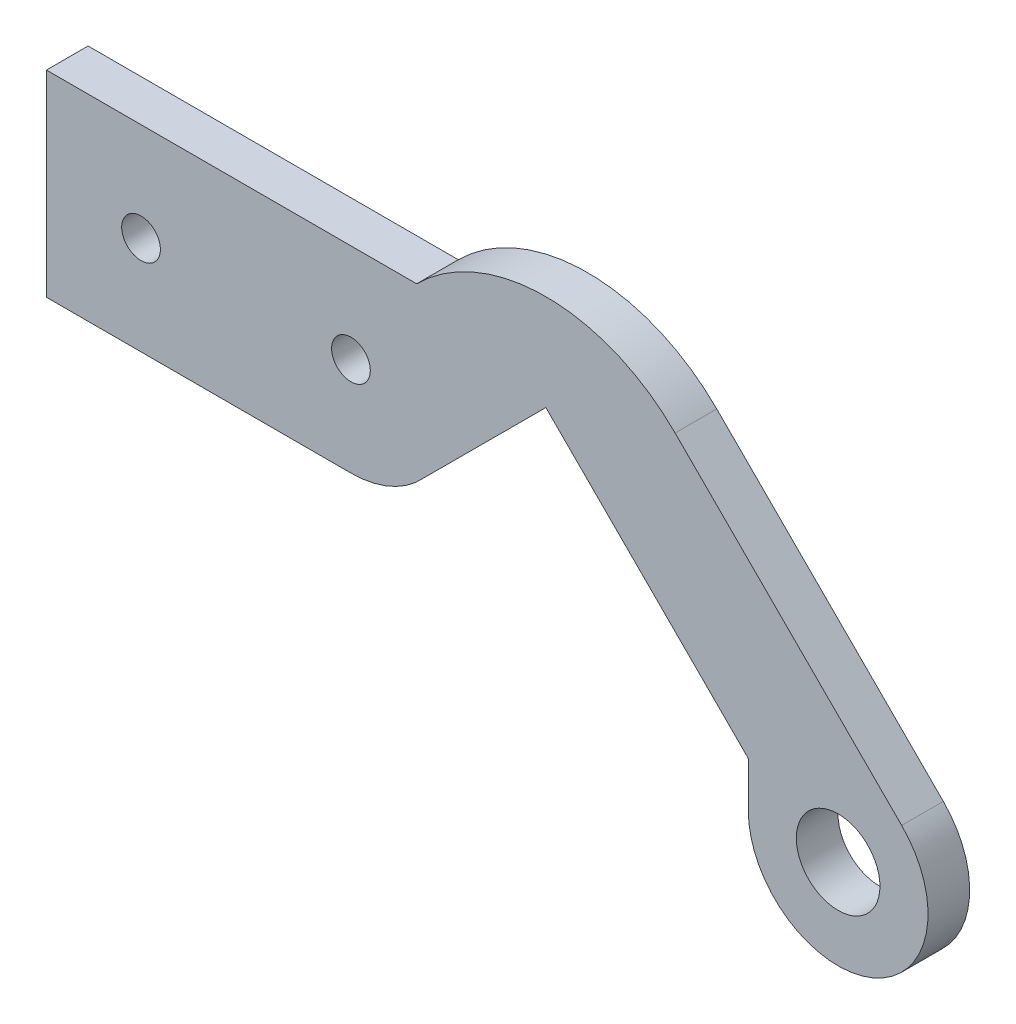
SolidWorks part; units mm, degrees
ref_plane "Front Plane" through (0, 0, 0) normal (0, 0, 1) x (1, 0, 0)
ref_plane "Top Plane" through (0, 0, 0) normal (0, 1, 0) x (1, 0, 0)
ref_plane "Right Plane" through (0, 0, 0) normal (1, 0, 0) x (0, 0, -1)
sketch "Sketch1" plane through (0, 0, 0) normal (0, 0, 1) x (1, 0, 0)
  line L0 (-37.5, 0) -> (37.5, 0)
  line L1 (-37.5, 0) -> (37.5, 0) construction
  line L2 (-37.5, 7.5) -> (37.5, 7.5)
  line L3 (-37.5, -7.5) -> (37.5, -7.5)
  arc A0 (-37.5, 7.5) -> (-37.5, -7.5) centre (-37.5, 0) ccw
  arc A1 (37.5, -7.5) -> (37.5, 7.5) centre (37.5, 0) ccw
  circle A2 centre (-37.5, 0) radius 3.175
  circle A3 centre (37.5, 0) radius 4.8
  point P0 (0, 0)
  point P4 (0, 0)
  dimension "D1" = 6.35
  dimension "D2" = 9.6
  dimension "D3" = 7.5
  dimension "D4" = 75
extrude "Boss-Extrude1" add sketch "Sketch1" along normal blind 3.175
sketch "Sketch2" plane through (0, 0, 3.175) normal (0, 0, 1) x (1, 0, 0)
  line L1 (-25, -1.3705) -> (-10, -1.3705)
  line L2 (-25, -1.3705) -> (-25, 1.8045)
  line L3 (-25, 1.8045) -> (-10, 1.8045)
  line L4 (-10, -1.3705) -> (-10, 1.8045)
  line L5 (-25, -1.3705) -> (-10, 1.8045) construction
  line L6 (-25, 1.8045) -> (-10, -1.3705) construction
  line L7 (10, -0.734) -> (25, -0.734)
  line L8 (10, -0.734) -> (10, 2.441)
  line L9 (10, 2.441) -> (25, 2.441)
  line L10 (25, -0.734) -> (25, 2.441)
  line L11 (10, -0.734) -> (25, 2.441) construction
  line L12 (10, 2.441) -> (25, -0.734) construction
  point P0 (-17.5, 0.217)
  point P5 (17.5, 0.8535)
  dimension "D1" = 3.175
  dimension "D2" = 3.175
  dimension "D3" = 15
  dimension "D4" = 15
  dimension "D5" = 20
  dimension "D6" = 10
extrude "Cut-Extrude1" cut sketch "Sketch2" against normal through all contours L2 L1 L4 L3 | L8 L7 L10 L9
sketch "Sketch3" plane through (0, 0, 3.175) normal (0, 0, 1) x (1, 0, 0)
  line L0 (-37.5, 0) -> (-20.71, 0)
  line L2 (-20.71, 0) -> (-56.5053, 0)
  line L3 (-20.71, 0) -> (-20.71, 17.1285)
  line L4 (-20.71, 17.1285) -> (-56.5053, 17.1285)
  line L5 (-56.5053, 0) -> (-56.5053, 17.1285)
  line L6 (-20.71, 0) -> (-56.5053, 0)
  line L7 (-20.71, 0) -> (-20.71, -10.2398)
  line L8 (-20.71, -10.2398) -> (-56.5053, -10.2398)
  line L9 (-56.5053, 0) -> (-56.5053, -10.2398)
  circle M3 centre (-37.5, 0) radius 3.175
  line M4 (-37.5, -7.5) -> (37.5, -7.5)
  line M6 (37.5, 7.5) -> (-37.5, 7.5)
  arc M7 (-37.5, 7.5) -> (-37.5, -7.5) centre (-37.5, 0) ccw
  line M12 (-25, -1.3705) -> (-25, 1.8045)
  line M13 (-25, 1.8045) -> (-10, 1.8045)
  line M15 (-10, -1.3705) -> (-25, -1.3705)
  dimension "D1" = 16.79
extrude "Cut-Extrude2" cut sketch "Sketch3" against normal blind 10 contours L5 L2 L3 L4 M7 M6 | L2 L9 L8 L7 M4 M7 | L3 L2 L0 M13 M6 M7 M3 M12 | L7 L0 L2 M15 M12 M3 M7 M4
sketch "Sketch4" plane through (0, 0, 3.175) normal (0, 0, 1) x (1, 0, 0)
  line L0 (-20.71, 1.8045) -> (-20.71, 7.5) construction
  line L1 (-20.71, 2.6568) -> (-9.1283, 2.6568)
  line L2 (-20.71, 2.6568) -> (-20.71, -2.9164)
  line L3 (-20.71, -2.9164) -> (-9.1283, -2.9164)
  line L4 (-9.1283, 2.6568) -> (-9.1283, -2.9164)
extrude "Boss-Extrude2" add sketch "Sketch4" against normal up to surface (3.175 mm away) up to face at (42.3, 0, 0)
sketch "Sketch5" plane through (0, 0, 3.175) normal (0, 0, 1) x (1, 0, 0)
  line L0 (-20.71, 7.5) -> (-20.71, -7.5) construction
  circle A0 centre (-13.5, 0) radius 1.475
  circle A1 centre (2.5, 0) radius 1.475
  dimension "D1" = 7.21
  dimension "D2" = 2.95
  dimension "D3" = 2.95
  dimension "D4" = 16
extrude "Cut-Extrude3" cut sketch "Sketch5" against normal blind 16
sketch "Sketch6" plane through (0, 0, 3.175) normal (0, 0, 1) x (1, 0, 0)
  line L1 (8.271, 4.3719) -> (29.5442, 4.3719)
  line L2 (8.271, 4.3719) -> (8.271, -3.0364)
  line L3 (8.271, -3.0364) -> (29.5442, -3.0364)
  line L4 (29.5442, 4.3719) -> (29.5442, -3.0364)
extrude "Boss-Extrude4" add sketch "Sketch6" against normal up to surface (3.175 mm away) up to face at (-12.025, 0, 0)
sketch "Sketch12" plane through (0, 0, 0) normal (0, 0, -1) x (-1, 0, 0)
  line L0 (-37.5, 7.5) -> (-2.5, 7.5)
  line L1 (-37.5, -7.5) -> (-2.5, -7.5)
  line L2 (20.71, -7.5) -> (20.71, 7.5) construction
  circle A0 centre (-2.5, 0) radius 7.5
  circle A1 centre (-2.5, 0) radius 1.475
  circle A2 centre (-37.5, 0) radius 7.5
  line M6 (20.71, 7.5) -> (-37.5, 7.5)
  arc M7 (-37.5, 7.5) -> (-37.5, -7.5) centre (-37.5, 0) ccw
  line M8 (-37.5, -7.5) -> (20.71, -7.5)
  circle M9 centre (-37.5, 0) radius 4.8
  dimension "D1" = 23.21
extrude "Cut-Extrude5" cut sketch "Sketch12" against normal blind 10 contours A2 A0 M8 M6 | A2 M7 M9
sketch "Sketch15" plane through (0, 0, 0) normal (0, 0, -1) x (-1, 0, 0)
  line L0 (-2.5, 7.5) -> (-43.314, -11.453)
  line L1 (-43.314, -11.453) -> (-35.9577, -17.7755)
  line L2 (-35.9577, -17.7755) -> (-2.5, -7.5)
  line L3 (-2.5, -7.5) -> (-2.5, 7.5)
  line L4 (-46.4858, -14.6142) -> (-39.6358, -21.4642)
  line L5 (-39.6358, -21.4642) -> (-43.0608, -18.0392)
  line L6 (-43.0608, -18.0392) -> (-47.4618, -22.4401)
  line L7 (-43.0608, -18.0392) -> (-32.0312, -7.0096)
  line L8 (-11.7911, 3.1854) -> (-8.23, 4.8391)
  circle A0 centre (-39.6358, -14.6142) radius 4.85
  circle A2 centre (-39.6358, -14.6142) radius 6.85
  arc A3 (-44.4795, -19.4579) -> (-2.5, 7.5) centre (-24.3855, -4.5841) cw
  circle A4 centre (-2.5, 0) radius 7.5
  arc A5 (-34.7398, -9.7182) -> (-10, 0) centre (-22.3699, -4.8591) cw
  arc A6 (-2.5, 7.5) -> (-2.5, -7.5) centre (-2.5, 0) ccw construction
  arc A7 (-10, 0) -> (-8.23, 4.8391) centre (-2.5, 0) cw
  arc A8 (-10, 0) -> (-11.7911, 3.1854) centre (-22.3699, -4.8591) ccw
  dimension "D5" = 25
  dimension "D6" = 13.2901
  dimension "D1" = 45
  dimension "D2" = 9.7
  dimension "D3" = 35
  dimension "D4" = 2
extrude "Boss-Extrude10" add sketch "Sketch15" against normal up to surface (3.175 mm away)
sketch "Sketch16" plane through (0, 0, 0) normal (0, 0, -1) x (-1, 0, 0)
  line L0 (-7.8033, -5.3033) -> (-21.5097, 8.4031)
  arc A0 (-10, 0) -> (-2.5, -7.5) centre (-2.5, 0) ccw construction
  arc A1 (-10, 0) -> (-34.7398, -9.7182) centre (-22.3699, -4.8591) ccw construction
  circle A2 centre (-14.6565, 1.5499) radius 9.6919
  arc M7 (-34.7398, -9.7182) -> (-10, 0) centre (-22.3699, -4.8591) cw
  arc M8 (-10, 0) -> (-2.5, -7.5) centre (-2.5, 0) ccw
extrude "Boss-Extrude11" add sketch "Sketch16" against normal up to surface (3.175 mm away) contours L0 M8 M7 up to face at (3.975, 0, 3.175)
sketch "Sketch17" plane through (0, 0, 0) normal (0, 0, -1) x (-1, 0, 0)
  line L0 (-34.7922, -9.7705) -> (-34.7398, -9.7182)
  line L1 (-34.7922, -9.7705) -> (-32.9259, -7.9042)
  line L2 (-34.7922, -9.7705) -> (-19.0641, 5.9575)
  line L3 (-7.8033, -5.3033) -> (-21.5097, 8.4031) construction
  line L4 (-19.0641, 5.9575) -> (-20.7559, 9.5193)
  line L5 (-20.7559, 9.5193) -> (-23.454, 8.6584)
  circle A1 centre (-26.9281, -1.9065) radius 11.1214
  line M2 (-21.5097, 8.4031) -> (-7.8033, -5.3033)
  line M9 (-34.7922, -9.7705) -> (-34.7398, -9.7182)
  arc M10 (-34.7398, -9.7182) -> (-21.5097, 8.4031) centre (-22.3699, -4.8591) cw
extrude "Boss-Extrude12" add sketch "Sketch17" against normal up to surface (3.175 mm away) contours A1 L4 L5 M10 M2 | A1 M2 M10 | L2 A1 L1 M10 | A1 M10 M9 up to face at (13.5062, -1.7017, 3.175)
sketch "Sketch18" plane through (0, 0, 0) normal (0, 0, -1) x (-1, 0, 0)
  line L0 (-49.3855, -4.5841) -> (-24.3855, 20.4159)
  line L1 (-49.3855, -4.5841) -> (-55.4039, 2.1365)
  line L2 (-55.4039, 2.1365) -> (-30.5677, 24.378)
  line L3 (-30.5677, 24.378) -> (-24.3855, 20.4159)
  arc A0 (-2.5, 7.5) -> (-46.0019, -17.1431) centre (-24.3855, -4.5841) ccw construction
extrude "Cut-Extrude6" cut sketch "Sketch18" against normal blind 10
sketch "Sketch19" plane through (0, 0, 0) normal (0, 0, -1) x (-1, 0, 0)
  line L0 (-39.6358, -14.6142) -> (-44.4795, -9.7705)
  line L1 (-44.4795, -9.7705) -> (-15.8099, 18.8991)
  line L2 (-45.042, -18.8208) -> (-55.9249, -16.9199)
  line L3 (-55.9249, -16.9199) -> (-55.2634, -4.1714)
  line L4 (-55.2634, -4.1714) -> (-13.4876, 33.4823)
  line L5 (-13.4876, 33.4823) -> (-15.8099, 18.8991)
  circle A0 centre (-39.6358, -14.6142) radius 6.85
  arc A1 (-2.5, 7.5) -> (-24.3855, 20.4159) centre (-24.3855, -4.5841) ccw construction
  arc M2 (-2.5, 7.5) -> (-24.3855, 20.4159) centre (-24.3855, -4.5841) ccw
  line M3 (-24.3855, 20.4159) -> (-49.3855, -4.5841)
  arc M4 (-49.3855, -4.5841) -> (-46.0019, -17.1431) centre (-24.3855, -4.5841) ccw
extrude "Cut-Extrude7" cut sketch "Sketch19" against normal blind 10 contours A0 L1 M2 M3 M4
sketch "Sketch20" plane through (0, 0, 0) normal (0, 0, -1) x (-1, 0, 0)
  line L0 (-32.7858, -14.6142) -> (-32.7858, -7.7642)
  line L1 (-34.7922, -9.7705) -> (-19.0641, 5.9575) construction
  line L2 (-46.4858, -14.6142) -> (-46.4858, -7.7642)
  line L3 (-46.4858, -7.7642) -> (-15.8099, 18.8991)
  line L4 (-46.4858, -14.6142) -> (-15.8099, 18.8991)
  line L5 (-35.5858, -9.4177) -> (-32.7858, -14.6142)
  arc A0 (-44.4795, -9.7705) -> (-34.7922, -9.7705) centre (-39.6358, -14.6142) ccw construction
  arc A1 (-32.7858, -7.7642) -> (-35.5858, -9.4177) centre (-32.7858, -10.9617) ccw
extrude "Boss-Extrude13" add sketch "Sketch20" against normal up to surface (3.175 mm away) contours L4 L3 L2 | L5 L0 A1 up to face at (3.975, 0, 3.175)
sketch "Sketch21" plane through (0, 0, 0) normal (0, 0, -1) x (-1, 0, 0)
  line L0 (-15.8099, 18.8991) -> (-3.4947, 5.1883)
  line L1 (-3.4947, 5.1883) -> (20.71, 7.5)
  arc A0 (20.71, 7.5) -> (-15.8099, 18.8991) centre (-12.3346, -34.1671) ccw
extrude "Boss-Extrude14" add sketch "Sketch21" against normal up to surface (3.175 mm away) up to face at (14.908, -2.8524, 3.175)
sketch "Sketch22" plane through (0, 0, 0) normal (0, 0, -1) x (-1, 0, 0)
  line L0 (-2.5, 7.5) -> (-19.0641, 5.9575)
  line L1 (-19.0641, 5.9575) -> (-7.8033, -5.3033)
  circle A0 centre (-2.5, 0) radius 7.5
  line M7 (-19.0641, 5.9575) -> (-7.8033, -5.3033)
extrude "Cut-Extrude8" cut sketch "Sketch22" against normal blind 10 contours A0 L0 M7
sketch "Sketch8" plane through (0, 0, 3.175) normal (0, 0, 1) x (1, 0, 0)
  line L1 (14, -1.5875) -> (24, -1.5875)
  line L2 (14, -1.5875) -> (14, 1.5875)
  line L3 (14, 1.5875) -> (24, 1.5875)
  line L4 (24, -1.5875) -> (24, 1.5875)
  line L5 (14, -1.5875) -> (24, 1.5875) construction
  line L6 (14, 1.5875) -> (24, -1.5875) construction
  point P0 (19, 0)
  dimension "D1" = 14
  dimension "D2" = 3.175
  dimension "D3" = 1.5875
  dimension "D4" = 10
extrude "Cut-Extrude4" cut sketch "Sketch8" against normal blind 10
sketch "Sketch24" plane through (0, 0, 0) normal (0, 0, -1) x (-1, 0, 0)
  line L0 (-32.7858, -7.7642) -> (-19.0641, 5.9575)
  line L1 (-19.0641, 5.9575) -> (-25.925, 1.8358)
  line L2 (-25.925, 1.8358) -> (-32.7858, -7.7642)
extrude "Boss-Extrude15" add sketch "Sketch24" against normal up to surface (3.175 mm away) up to face at (18.1178, -1.532, 3.175)
sketch "Sketch25" plane through (0, 0, 0) normal (0, 0, -1) x (-1, 0, 0)
  line L0 (-39.6358, -9.7642) -> (-44.4858, -14.6142)
  line L1 (-44.4858, -14.6142) -> (-42.0608, -12.1892)
  line L2 (-42.0608, -12.1892) -> (-49.4465, -4.8036)
  line L3 (-39.6358, -9.7642) -> (-44.4795, -9.7705)
  line L4 (-42.0608, -9.3608) -> (-42.0608, -9.3608)
  line L5 (-44.4795, -9.7705) -> (-15.8099, 18.8991)
  line L6 (-42.0608, -9.3608) -> (-48.0323, -3.3894) construction
  line L7 (-41.0501, -8.35) -> (-42.0608, -9.3608) construction
  line L8 (-15.8099, 18.8991) -> (-62.9613, 8.7112)
  line L9 (-62.9613, 8.7112) -> (-46.4858, -14.6142)
  circle A0 centre (-39.6358, -14.6142) radius 4.85
  circle A1 centre (-39.6358, -14.6142) radius 6.85
  dimension "D1" = 2
extrude "Cut-Extrude10" cut sketch "Sketch25" against normal blind 10
sketch "Sketch26" plane through (0, 0, 0) normal (0, 0, -1) x (-1, 0, 0)
  line L0 (-19.0641, 5.9575) -> (-23.9078, 10.8012)
  line L1 (-44.4795, -9.7705) -> (-15.8099, 18.8991) construction
  line L2 (-23.9078, 10.8012) -> (-24.4629, 21.1534)
  line L3 (-24.4629, 21.1534) -> (12.5105, 32.5108)
  line L4 (12.5105, 32.5108) -> (20.5457, 7.6298)
  arc A0 (-23.9078, 10.8012) -> (20.5457, 7.6298) centre (-4.4631, -29.7809) cw
  arc A1 (20.71, 7.5) -> (-15.8099, 18.8991) centre (-12.3346, -34.1671) ccw construction
  arc M1 (20.71, 7.5) -> (-15.8099, 18.8991) centre (-12.3346, -34.1671) ccw
  line M2 (-15.8099, 18.8991) -> (-44.4795, -9.7705)
  dimension "D1" = 45
extrude "Cut-Extrude11" cut sketch "Sketch26" against normal blind 10 contours A0 M2 M1 | L4 L3 L2 M2 M1
sketch "Sketch27" plane through (0, 0, 0) normal (0, 0, -1) x (-1, 0, 0)
  line L0 (-9.9677, -0.6954) -> (-2.5, -7.5)
  line L1 (-2.5, -7.5) -> (-6.2338, -4.0977)
  line L2 (-6.2338, -4.0977) -> (-9.9677, -8.1954)
  line L3 (-2.5, -7.5) -> (-7.5515, -5.5437)
  line L4 (-7.5515, -5.5437) -> (-19.0641, 5.9575)
  line L5 (-19.0641, 5.9575) -> (-2.5, 9.0718)
  line L6 (-2.5, 9.0718) -> (-4.8631, 2.7586)
  line L7 (-4.8631, 2.7586) -> (-9.9677, -0.6954)
  arc A0 (-3.8848, 7.371) -> (-2.5, -7.5) centre (-2.5, 0) ccw construction
  line M10 (-19.0641, 5.9575) -> (-3.8848, 7.371)
  arc M11 (-3.8848, 7.371) -> (-2.5, -7.5) centre (-2.5, 0) ccw
extrude "Boss-Extrude16" add sketch "Sketch27" against normal up to surface (3.175 mm away) contours L4 M11 M10 up to face at (44.4858, -14.6142, 3.175)
sketch "Sketch28" plane through (0, 0, 0) normal (0, 0, -1) x (-1, 0, 0)
  line L0 (20.71, 7.5) -> (-23.9078, 10.8012)
  line L1 (-23.9078, 10.8012) -> (-10.7304, 19.8986)
  line L2 (-10.7304, 19.8986) -> (15.1582, 17.0435)
  line L3 (15.1582, 17.0435) -> (20.71, 7.5)
extrude "Cut-Extrude12" cut sketch "Sketch28" against normal up to surface (3.175 mm away) up to face at (10.5058, -2.3762, 3.175)
sketch "Sketch29" plane through (0, 0, 0) normal (0, 0, -1) x (-1, 0, 0)
  line L0 (-19.0641, 5.9575) -> (-32.7858, -7.7642)
  line L1 (-32.7858, -7.7642) -> (-32.7858, -11.1892)
  line L2 (-32.7858, -14.6142) -> (-32.7858, -7.7642) construction
  line L3 (-32.7858, -11.1892) -> (-17.3584, 4.2535)
  line L4 (-8.0387, -5.057) -> (-19.0641, 5.9575) construction
  line L5 (-17.3584, 4.2535) -> (-19.0641, 5.9575)
extrude "Boss-Extrude18" add sketch "Sketch29" against normal up to surface (3.175 mm away) up to face at (14.0026, -4.1424, 3.175)
sketch "Sketch30" plane through (0, 0, 0) normal (0, 0, -1) x (-1, 0, 0)
  line L0 (20.71, 7.5) -> (-29.7262, 7.5)
  line L1 (-29.7262, 7.5) -> (-24.0206, 17.421)
  line L2 (-24.0206, 17.421) -> (20.71, 7.5)
extrude "Cut-Extrude13" cut sketch "Sketch30" against normal up to surface (3.175 mm away) contours L2 L0 L1 up to face at (13.8131, -4.7122, 3.175)
sketch "Sketch31" plane through (0, 0, 0) normal (0, 0, -1) x (-1, 0, 0)
  line L0 (20.71, 7.5) -> (-27.209, 7.5) construction
  line L1 (-27.209, 7.5) -> (-7.5079, 7.5)
  arc A1 (-27.209, 7.5) -> (-7.5079, 7.5) centre (-17.3584, -2.3506) cw
extrude "Boss-Extrude19" add sketch "Sketch31" against normal up to surface (3.175 mm away) up to face at (44.4858, -14.6142, 3.175)
sketch "Sketch32" plane through (0, 0, 0) normal (0, 0, -1) x (-1, 0, 0)
  circle A0 centre (-39.6358, -14.6142) radius 3.1875
  circle A1 centre (-39.6358, -14.6142) radius 6.7162
  dimension "D1" = 6.375
extrude "Boss-Extrude20" add sketch "Sketch32" against normal up to surface (3.175 mm away) up to face at (44.4858, -14.6142, 3.175)
